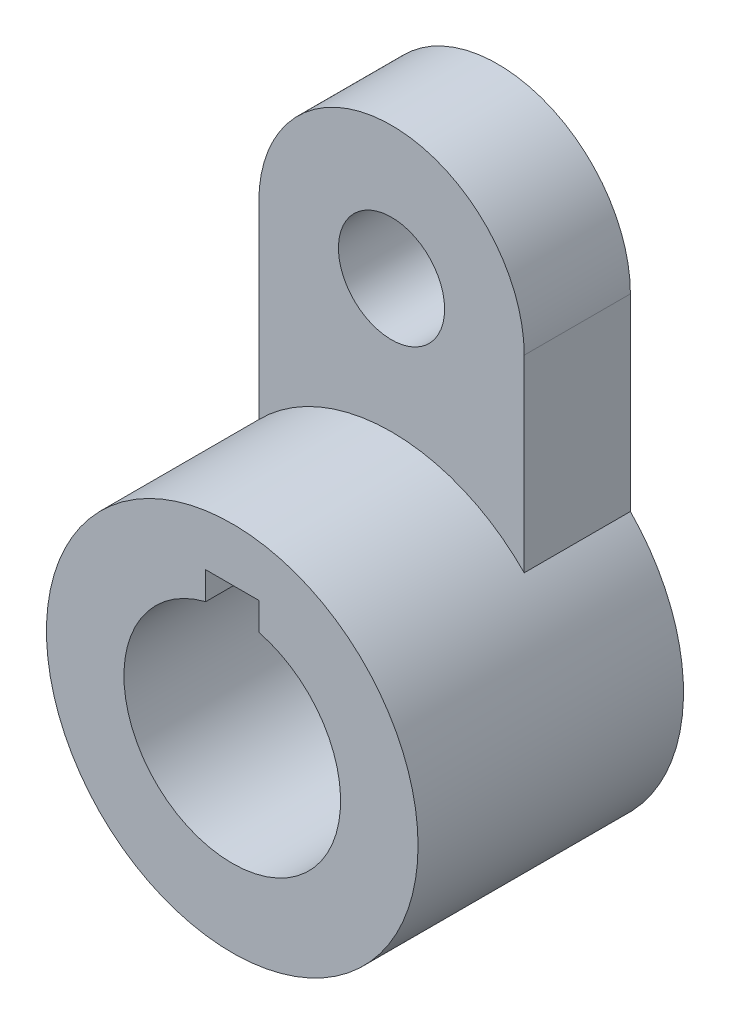
SolidWorks part; units mm, degrees
material "1060 Alloy"
ref_plane "Front Plane" through (0, 0, 0) normal (0, 0, 1) x (1, 0, 0)
ref_plane "Top Plane" through (0, 0, 0) normal (0, 1, 0) x (1, 0, 0)
ref_plane "Right Plane" through (0, 0, 0) normal (1, 0, 0) x (0, 0, -1)
sketch "Sketch1" plane through (0, 0, 0) normal (0, 0, 1) x (1, 0, 0)
  circle A0 centre (0, 0) radius 22.225
extrude "Boss-Extrude1" add sketch "Sketch1" along normal blind 31.75
sketch "Sketch2" plane through (0, 0, 0) normal (0, 0, 1) x (1, 0, 0)
  line L0 (-15.875, 7.2717) -> (15.875, 7.2717)
  line L1 (15.875, 7.2717) -> (15.875, 38.1)
  line L2 (-15.875, 7.2717) -> (-15.875, 38.1)
  arc A0 (15.875, 38.1) -> (-15.875, 38.1) centre (0, 38.1) ccw
  circle A1 centre (0, 38.1) radius 6.35
  dimension "D2" = 15.875
  dimension "D3" = 12.7
  dimension "D1" = 38.1
extrude "Boss-Extrude2" add sketch "Sketch2" along normal blind 12.7
sketch "Sketch3" plane through (0, 0, 31.75) normal (0, 0, 1) x (1, 0, 0)
  line L0 (-3.175, 12.564) -> (-3.175, 15.875)
  line L1 (-3.175, 15.875) -> (3.175, 15.875)
  line L2 (3.175, 15.875) -> (3.175, 12.564)
  arc A0 (-3.175, 12.564) -> (3.175, 12.564) centre (0, 0) ccw
  dimension "D1" = 3.175
  dimension "D2" = 3.175
  dimension "D3" = 15.875
extrude "Cut-Extrude1" cut sketch "Sketch3" against normal through all
